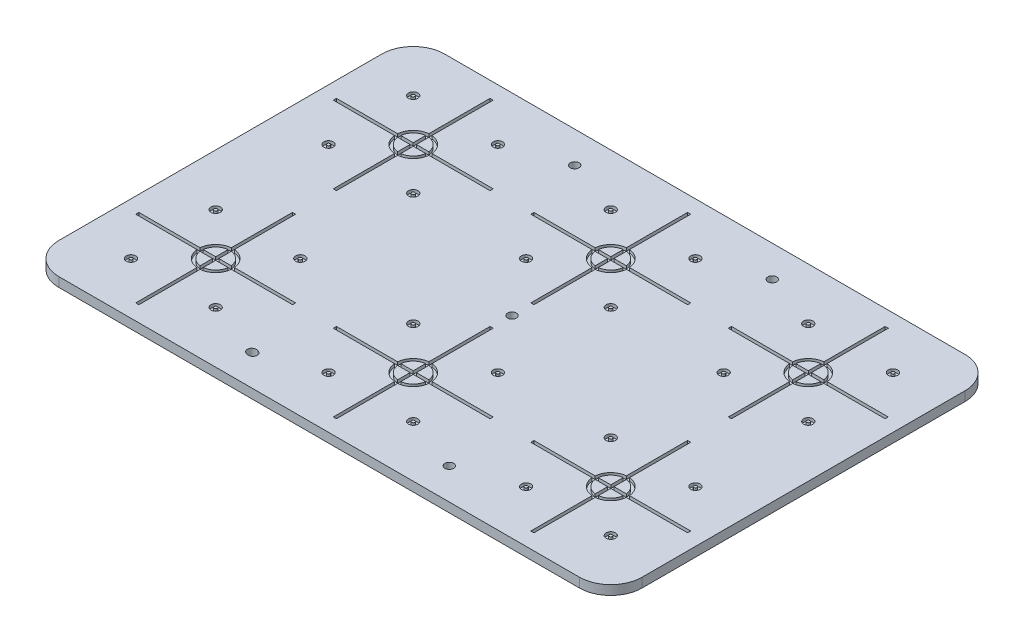
SolidWorks part; units mm, degrees
material "6063-O"
ref_plane "Front" through (0, 0, 0) normal (0, 0, 1) x (1, 0, 0)
ref_plane "Top" through (0, 0, 0) normal (0, 1, 0) x (1, 0, 0)
ref_plane "Right" through (0, 0, 0) normal (1, 0, 0) x (0, 0, -1)
sketch "Sketch1" plane through (0, 0, 0) normal (0, 1, 0) x (1, 0, 0)
  line L1 (83, 61.5) -> (-83, 61.5)
  line L2 (93, 51.5) -> (93, -51.5)
  line L3 (83, -61.5) -> (-83, -61.5)
  line L4 (-93, 51.5) -> (-93, -51.5)
  line L5 (93, 61.5) -> (-93, -61.5) construction
  line L6 (93, -61.5) -> (-93, 61.5) construction
  arc A0 (-83, -61.5) -> (-93, -51.5) centre (-83, -51.5) cw
  arc A1 (93, -51.5) -> (83, -61.5) centre (83, -51.5) cw
  arc A2 (83, 61.5) -> (93, 51.5) centre (83, 51.5) cw
  arc A3 (-83, 61.5) -> (-93, 51.5) centre (-83, 51.5) ccw
  point P0 (0, 0)
  dimension "D3" = 10
  dimension "D1" = 123
  dimension "D2" = 186
extrude "Boss-Extrude1" add sketch "Sketch1" along normal blind 3
sketch "Sketch2" plane through (0, 3, 0) normal (0, 1, 0) x (1, 0, 0)
  line L0 (-50.3327, 31.5) -> (-108.107, 31.5) construction
  line L2 (-88, 31.5) -> (-38, 31.5)
  line L3 (-63, 56.5) -> (-63, 6.5)
  line L6 (83, 61.5) -> (-83, 61.5) construction
  line L7 (-93, 51.5) -> (-93, -51.5) construction
  circle A0 centre (-63, 31.5) radius 25
  circle A1 centre (-76.5, 45) radius 1
  circle A2 centre (-49.5, 45) radius 1
  circle A3 centre (-63, 31.5) radius 5
  circle A4 centre (-49.5, 18) radius 1
  circle A5 centre (-76.5, 18) radius 1
  dimension "D1" = 50
  dimension "D4" = 10
  dimension "D5" = 27
  dimension "D2" = 30
  dimension "D3" = 30
  dimension "D8" = 2
  dimension "D6" = 27
  dimension "D7" = 13.5
extrude "Cut-Extrude-Thin1" cut sketch "Sketch2" against normal blind 1 thin
pattern_linear "LPattern1" count 3 spacing 63 along (1, 0, 0) count 2 spacing 63 along (0, 0, 1) of "Cut-Extrude-Thin1"
hole_wizard "#3 Clearance Hole2" positions "Sketch5" profile "Sketch6" hole size "#3" standard "ANSI Inch" end condition through all
sketch "Sketch5" plane through (0, 3, 0) normal (0, 1, 0) x (1, 0, 0)
  line L0 (-93, 51.5) -> (-93, -51.5) construction
  line L1 (83, 61.5) -> (-83, 61.5) construction
  line L2 (93, -51.5) -> (93, 51.5) construction
  line L3 (-83, -61.5) -> (83, -61.5) construction
  point P0 (-31.5, 51.5)
  point P2 (31.5, 51.5)
  point P4 (31.5, -51.5)
  point P8 (-31.5, -51.5)
  point P20 (-31.037, -51.6158)
  point P22 (0, 0)
  dimension "D1" = 61.5
  dimension "D2" = 10
  dimension "D3" = 10
  dimension "D4" = 61.5
  dimension "D5" = 10
  dimension "D6" = 61.5
  dimension "D7" = 61.5
  dimension "D8" = 10
sketch "Sketch6" plane through (-31.5, 3, -51.5) normal (1, 0, 0) x (0, 0, 1)
  line L0 (0, 0) -> (0, 3)
  line L1 (0, 3) -> (1.397, 3)
  line L2 (1.397, 3) -> (1.397, 0)
  line L5 (1.397, 0) -> (0, 0)
  line L11 (0, -6.35) -> (0, 107.95) construction
  dimension "Thru Hole Dia." = 2.794
  dimension "Thru Hole Depth" = 3
hole_wizard "#3 Clearance Hole1" positions "Sketch3" profile "Sketch4" hole size "#3" standard "ANSI Inch"
sketch "Sketch3" plane through (28.8202, 3, -15.8405) normal (0, 1, 0) x (1, 0, 0)
  point P0 (-28.8202, -15.8405)
  point P1 (34.1798, 35.6595)
  point P2 (-91.8202, 35.6595)
  point P3 (-91.8202, -67.3405)
  point P4 (34.1798, -67.3405)
sketch "Sketch4" plane through (0, 3, 0) normal (1, 0, 0) x (0, 0, 1)
  line L0 (0, 0) -> (0, 3)
  line L1 (0, 3) -> (1.397, 3)
  line L2 (1.397, 3) -> (1.397, 0)
  line L3 (1.397, 0) -> (0, 0)
  line L4 (0, -6.35) -> (0, 107.95) construction
  dimension "Thru Hole Dia." = 2.794
  dimension "Thru Hole Depth" = 3
